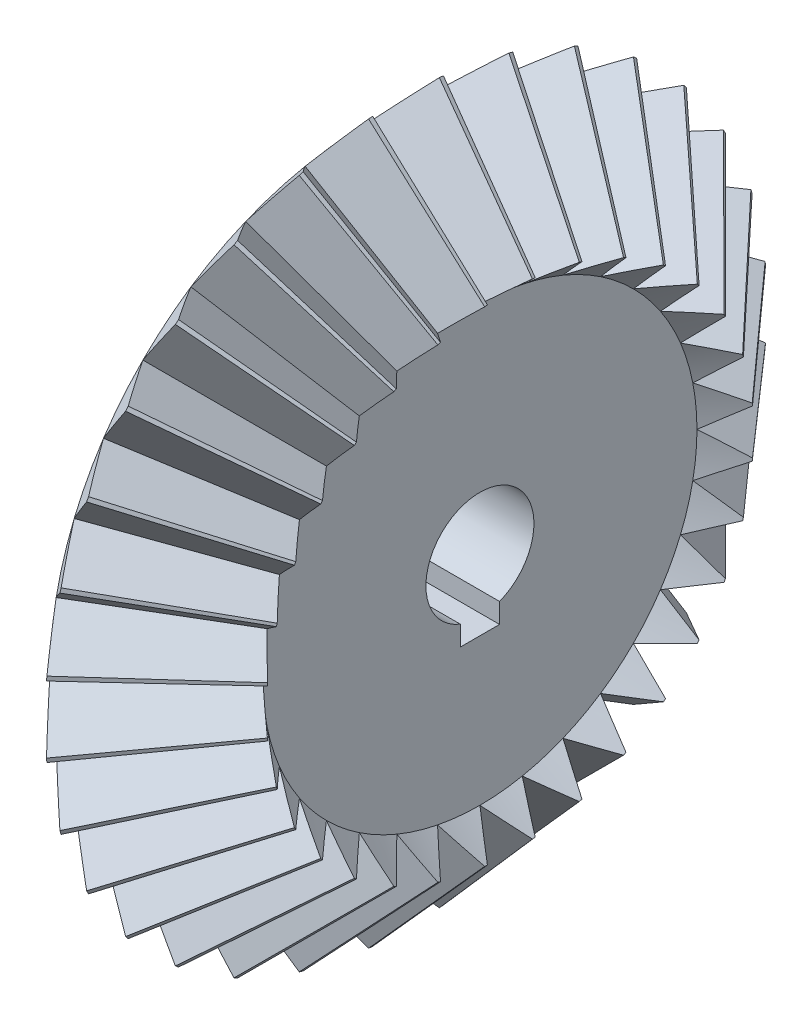
SolidWorks part; units mm, degrees
ref_plane "Front Plane" through (0, 0, 0) normal (0, 0, 1) x (1, 0, 0)
ref_plane "Top Plane" through (0, 0, 0) normal (0, 1, 0) x (1, 0, 0)
ref_plane "Right Plane" through (0, 0, 0) normal (1, 0, 0) x (0, 0, -1)
sketch "Sketch1" plane through (0, 0, 0) normal (0, 1, 0) x (1, 0, 0)
  line L2 (0, 0) -> (23, 0)
  line L3 (0, 0) -> (0, 64.5308)
  line L4 (0, 64.5308) -> (23, 64.5308) construction
  line L5 (23, 0) -> (23, 64.5308) construction
  line L9 (0, 64.5308) -> (23, 44.1992) construction
  line L10 (23, 44.1992) -> (73, 0) construction
  line L11 (73, 0) -> (29.1094, 49.6048) construction
  line L12 (29.1094, 49.6048) -> (7.9477, 73.5215)
  line L13 (7.9477, 73.5215) -> (0, 64.5308)
  line L14 (23, 0) -> (73, 0) construction
  line L15 (29.1094, 49.6048) -> (23, 44.1992)
  line L16 (3.9738, 69.0262) -> (73, 0) construction
  line L17 (23, 44.1992) -> (23, 0)
  point P0 (0, 0)
  point P2 (3.9738, 69.0262)
  dimension "D1" = 73
  dimension "D3" = 23
  dimension "D4" = 45
  dimension "D5" = 12
revolve "Revolve1" add sketch "Sketch1" angle 360 about L14
ref_plane "Plane3" through (-32.0216, 0, -28.3065) normal (-0.7492, 0, -0.6623) x (-0.6623, 0, 0.7492)
sketch "Sketch8" plane through (-32.0216, 0, -28.3065) normal (-0.7492, 0, -0.6623) x (-0.6623, 0, 0.7492)
  line L0 (-48.3485, 0) -> (-60.1129, -6.7922)
  line L1 (-60.1129, -6.7922) -> (-60.1129, 6.7922)
  line L2 (-60.1129, 6.7922) -> (-48.3485, 0)
  line L4 (-60.1129, -6.7922) -> (-73.6973, -6.7922)
  line L5 (-60.1129, -6.7922) -> (-60.1129, 6.7922)
  line L6 (-60.1129, 6.7922) -> (-73.6973, 6.7922)
  line L7 (-73.6973, -6.7922) -> (-73.6973, 6.7922)
  ellipse E0 centre (0, 0) end of major axis (0, -64.5308) minor radius 48.3485 construction
  ellipse E1 centre (-5.2638, 0) end of major axis (-5.2638, -73.5215) minor radius 55.0847 construction
  point P9 (-66.736, 6.545)
  dimension "D1" = 60
extrude "Cut-Extrude3" cut sketch "Sketch8" against normal through all contours L2 L1 L0 | L7 L4 L1 L6
pattern_circular "CirPattern2" count 32 over 360 about axis through (0, 0, 0) along (1, 0, 0) of "Cut-Extrude3"
sketch "Sketch5" plane through (0, 0, 0) normal (-1, 0, 0) x (0, 0, 1)
  circle A0 centre (0, 0) radius 20
  dimension "D1" = 40
extrude "Boss-Extrude2" add sketch "Sketch5" along normal blind 12
sketch "Sketch6" plane through (-12, 0, 0) normal (-1, 0, 0) x (0, 0, 1)
  line L1 (-4, -10.247) -> (4, -10.247)
  line L2 (-4, -10.247) -> (-4, -14.3)
  line L3 (-4, -14.3) -> (4, -14.3)
  line L4 (4, -10.247) -> (4, -14.3)
  circle A0 centre (0, 0) radius 11
  point P8 (0, -10.247)
  dimension "D1" = 22
  dimension "D2" = 14.3
  dimension "D3" = 8
extrude "Cut-Extrude1" cut sketch "Sketch6" against normal up to surface (35 mm away) contours L1 A0 | A0 L2 L3 L4 | L1 A0 up to face at (23, 0, 0)
